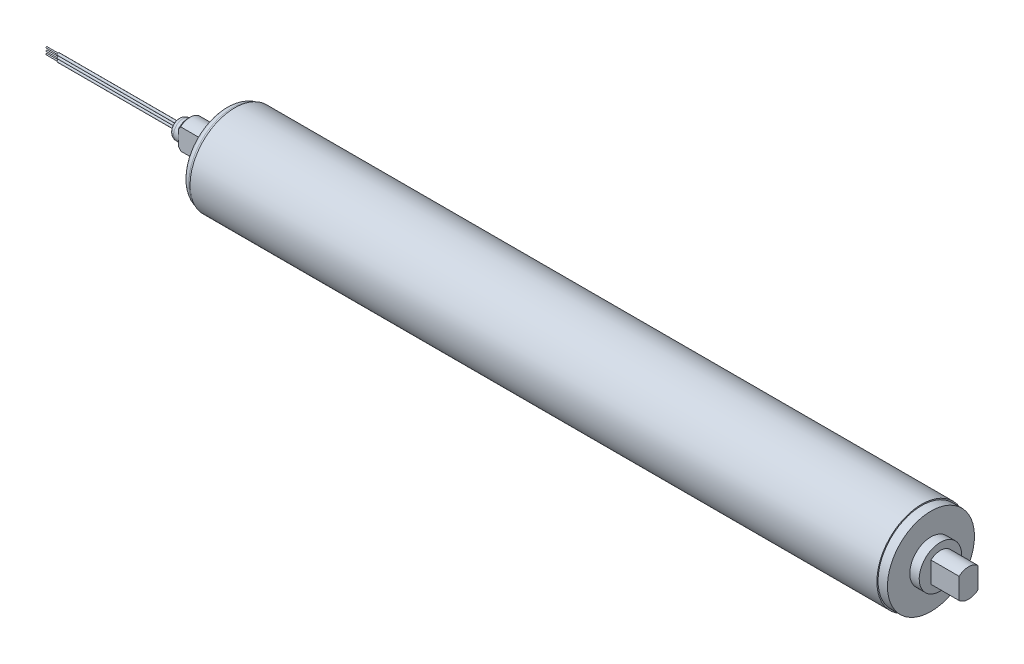
SolidWorks part; units mm, degrees
ref_plane "Front Plane" through (0, 0, 0) normal (0, 0, 1) x (1, 0, 0)
ref_plane "Top Plane" through (0, 0, 0) normal (0, 1, 0) x (1, 0, 0)
ref_plane "Right Plane" through (0, 0, 0) normal (1, 0, 0) x (0, 0, -1)
ref_plane "Plane1" through (4, 0, 0) normal (1, 0, 0) x (0, 0, -1)
ref_plane "Plane2" through (-304, 0, 0) normal (1, 0, 0) x (0, 0, -1)
sketch "Sketch2" plane through (0, 0, 0) normal (0, 0, 1) x (1, 0, 0)
  line L0 (-4, 18.5) -> (0, 18.5)
  line L1 (-296, 19) -> (-4, 19)
  line L2 (-296, 19) -> (-296, 18.5)
  line L3 (-296, -19) -> (-4, -19) construction
  line L4 (-4, 19) -> (-4, 18.5)
  line L5 (0, 18.5) -> (0, 9)
  line L6 (0, -18.5) -> (-4, -18.5) construction
  line L7 (0, 9) -> (4, 9)
  line L8 (4, 9) -> (4, 6)
  line L9 (4, -9) -> (0, -9) construction
  line L10 (4, 6) -> (16, 6)
  line L11 (16, 6) -> (16, 0)
  line L12 (16, -6) -> (4, -6) construction
  line L13 (0, 0) -> (-320, 0) construction
  line L14 (-296, 18.5) -> (-297, 18.5)
  line L15 (-300, 15.5) -> (-300, 9)
  line L16 (-300, -18.5) -> (-296, -18.5) construction
  line L17 (-300, 9) -> (-303.2, 9)
  line L18 (-304, 8.2) -> (-304, 6)
  line L19 (-304, -9) -> (-300, -9) construction
  line L20 (-320, 0) -> (16, 0)
  line L21 (-316, 5) -> (-316, 4)
  line L22 (-316, -6) -> (-304, -6) construction
  line L23 (-315, 6) -> (-316, 5)
  line L24 (-304, -6) -> (-304, -9) construction
  line L25 (-300, -9) -> (-300, -18.5) construction
  line L26 (-296, -18.5) -> (-296, -19) construction
  line L27 (-4, -18.5) -> (-4, -19) construction
  line L28 (0, -9) -> (0, -18.5) construction
  line L29 (4, -6) -> (4, -9) construction
  line L30 (-316, -6) -> (-316, 0) construction
  line L31 (16, -6) -> (16, 0) construction
  line L32 (-303.2, 9) -> (-304, 8.2)
  line L33 (-316, 4) -> (-318, 4)
  line L34 (-320, 2) -> (-320, 0)
  line L35 (-320, -4) -> (-316, -4) construction
  line L37 (-320, 0) -> (-320, -4) construction
  line L38 (-316, -4) -> (-316, -6) construction
  line L39 (-315, 6) -> (-304, 6)
  arc A0 (-318, 4) -> (-320, 2) centre (-318, 2) ccw
  arc A1 (-297, 18.5) -> (-300, 15.5) centre (-297, 15.5) ccw
  point P24 (-304, 9)
  point P40 (-316, 6)
  dimension "FIX_7" = 3
  dimension "FIX_12" = 2
  dimension "D" = 38
  dimension "KSS_1" = 37
  dimension "G" = 18
  dimension "FIX_4" = 4
  dimension "FIX_3" = 16
  dimension "L" = 300
  dimension "FIX_1" = 4
  dimension "F" = 16
  dimension "FIX_2" = 4
  dimension "FIX_5" = 4
  dimension "FIX_10" = 8
  dimension "FIX_11" = 4
revolve "Revolve2" add sketch "Sketch2" angle 360 about L20
sketch "Sketch3" plane through (4, 0, 0) normal (1, 0, 0) x (0, 0, -1)
  line L0 (0, 6) -> (0, -6) construction
  line L1 (-4, 4.4721) -> (-4, -4.4721)
  line L2 (4, 4.4721) -> (4, -4.4721)
  arc A0 (-4, 4.4721) -> (-4, -4.4721) centre (0, 0) ccw
  arc A1 (4, -4.4721) -> (4, 4.4721) centre (0, 0) ccw
extrude "Cut-Extrude1" cut sketch "Sketch3" along normal through all
sketch "Sketch4" plane through (-304, 0, 0) normal (1, 0, 0) x (0, 0, -1)
  line L0 (0, 6) -> (0, -6) construction
  line L1 (-4, 4.4721) -> (-4, -4.4721)
  line L2 (4, 4.4721) -> (4, -4.4721)
  arc A0 (-4, 4.4721) -> (-4, -4.4721) centre (0, 0) ccw
  arc A1 (4, -4.4721) -> (4, 4.4721) centre (0, 0) ccw
extrude "Cut-Extrude2" cut sketch "Sketch4" against normal through all
sketch "Sketch8" plane through (0, 0, 0) normal (0, 0, 1) x (1, 0, 0)
  line L0 (-377.6154, 1.25) -> (-314.8593, 1.25) construction
  line L1 (-316, 1.75) -> (-371, 1.75)
  line L2 (-316, 1.75) -> (-316, 1.25)
  line L3 (-316, 1.25) -> (-376, 1.25)
  line L4 (-371, 1.75) -> (-371, 1.5)
  line L5 (-371, 1.5) -> (-376, 1.5)
  line L8 (-376, 1.5) -> (-376, 1.25)
  dimension "FIX_13" = 60
  dimension "FIX_17" = 5
  dimension "FIX_15" = 1
  dimension "FIX_14" = 0.5
  dimension "KSS_3" = 316
  dimension "FIX_16" = 1.25
revolve "Revolve3" add sketch "Sketch8" angle 360 about L0
pattern_linear "LPattern1" count 3 spacing 1.25 along (0, -1, 0) of "Revolve3"
equation "\"KSS_1@Sketch2\"=\"D@Sketch2\"-1"
equation "\"KSS_2@Plane2\"= \"L@Sketch2\" + \"FIX_1@Sketch2\""
equation "\"KSS_3@Sketch8\"= \"L@Sketch2\" + \"F@Sketch2\""
